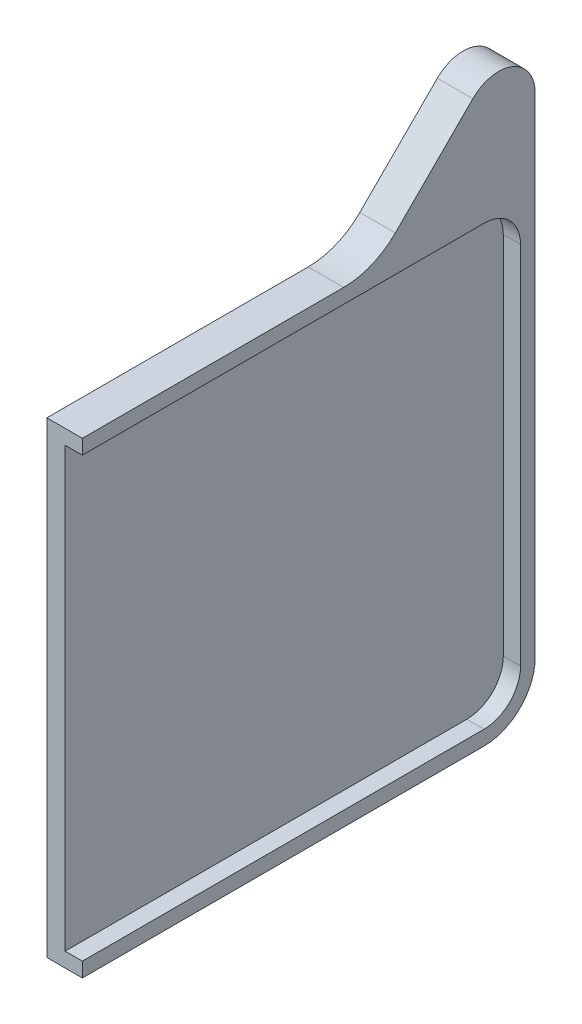
SolidWorks part; units mm, degrees
ref_plane "Front Plane" through (0, 0, 0) normal (0, 0, 1) x (1, 0, 0)
ref_plane "Top Plane" through (0, 0, 0) normal (0, 1, 0) x (1, 0, 0)
ref_plane "Right Plane" through (0, 0, 0) normal (1, 0, 0) x (0, 0, -1)
sketch "Sketch1" plane through (35.1028, 0, 0) normal (-1, 0, 0) x (0, 0, 1)
  line L0 (-114.3, 38.1) -> (-114.3, -38.1)
  line L1 (-114.3, 38.1) -> (-184.15, 38.1)
  line L2 (-190.5, 31.75) -> (-190.5, -31.75)
  line L3 (-184.15, -38.1) -> (-114.3, -38.1)
  line L4 (190.5, -31.75) -> (190.5, 31.75)
  line L5 (184.15, 38.1) -> (-184.15, 38.1)
  line L6 (-190.5, 31.75) -> (-190.5, -31.75)
  line L7 (-184.15, -38.1) -> (184.15, -38.1)
  line L8 (190.5, -31.75) -> (190.5, 31.75) construction
  line L9 (184.15, 38.1) -> (-184.15, 38.1) construction
  line L10 (-190.5, 31.75) -> (-190.5, -31.75) construction
  line L11 (-184.15, -38.1) -> (184.15, -38.1) construction
  arc A0 (-190.5, -31.75) -> (-184.15, -38.1) centre (-184.15, -31.75) ccw
  arc A1 (-190.5, 31.75) -> (-184.15, 38.1) centre (-184.15, 31.75) cw
  arc A4 (184.15, -38.1) -> (190.5, -31.75) centre (184.15, -31.75) ccw
  arc A5 (190.5, 31.75) -> (184.15, 38.1) centre (184.15, 31.75) ccw
  arc A6 (-184.15, 38.1) -> (-190.5, 31.75) centre (-184.15, 31.75) ccw
  arc A7 (-190.5, -31.75) -> (-184.15, -38.1) centre (-184.15, -31.75) ccw
  arc A8 (184.15, -38.1) -> (190.5, -31.75) centre (184.15, -31.75) ccw construction
  arc A9 (190.5, 31.75) -> (184.15, 38.1) centre (184.15, 31.75) ccw construction
  arc A10 (-184.15, 38.1) -> (-190.5, 31.75) centre (-184.15, 31.75) ccw construction
  arc A11 (-190.5, -31.75) -> (-184.15, -38.1) centre (-184.15, -31.75) ccw construction
  dimension "D2" = 76.2
  dimension "D1" = 0
extrude "Boss-Extrude1" add sketch "Sketch1" along normal blind 3.175 contours L0 L3 A0 L2 A1 L1
ref_plane "Plane1" through (35.1028, 38.1, -184.15) normal (0, 0, -1) x (-1, 0, 0)
sketch "Sketch4" plane through (31.9278, 0, 0) normal (-1, 0, 0) x (0, 0, 1)
  line L4 (-114.3, 38.1) -> (-184.15, 38.1)
  line L5 (-190.5, 31.75) -> (-190.5, -31.75)
  line L6 (-184.15, -38.1) -> (-114.3, -38.1)
  line L7 (-114.3, -38.1) -> (-114.3, 38.1)
  line L8 (-114.3, 38.1) -> (-184.15, 38.1)
  line L9 (-190.5, 31.75) -> (-190.5, -31.75)
  line L10 (-184.15, -38.1) -> (-114.3, -38.1)
  line L11 (-114.3, -38.1) -> (-114.3, 38.1) construction
  arc A2 (-184.15, 38.1) -> (-190.5, 31.75) centre (-184.15, 31.75) ccw
  arc A3 (-190.5, -31.75) -> (-184.15, -38.1) centre (-184.15, -31.75) ccw
  arc A4 (-184.15, 38.1) -> (-190.5, 31.75) centre (-184.15, 31.75) ccw
  arc A5 (-190.5, -31.75) -> (-184.15, -38.1) centre (-184.15, -31.75) ccw
  dimension "D1" = 0
extrude "Extrude-Thin1" add sketch "Sketch4" against normal up to surface (6.1722 mm away) thin
sketch "Sketch5" plane through (31.9278, 0, 0) normal (-1, 0, 0) x (0, 0, 1)
  line L0 (-177.8, 12.7) -> (-120.65, 12.7) construction
  line L1 (-177.8, 15.875) -> (-171.45, 15.875)
  line L2 (-177.8, 9.525) -> (-171.45, 9.525)
  line L3 (-171.45, 15.875) -> (-170.3501, 15.24)
  line L6 (-114.3, 0) -> (-193.04, 0) construction
  line L7 (-114.3, 40.64) -> (-114.3, -40.64) construction
  line L8 (-193.04, 31.75) -> (-193.04, -31.75) construction
  line L9 (-170.3501, 15.24) -> (-128.0999, 15.24)
  line L10 (-128.0999, 15.24) -> (-127, 15.875)
  line L11 (177.8, -15.875) -> (-177.8, -15.875)
  line L12 (-177.8, -22.225) -> (177.8, -22.225)
  line L13 (190.5, -31.75) -> (190.5, 31.75)
  line L14 (184.15, 38.1) -> (-184.15, 38.1)
  line L15 (-190.5, 31.75) -> (-190.5, -31.75)
  line L16 (-184.15, -38.1) -> (184.15, -38.1)
  line L17 (190.5, -31.75) -> (190.5, 31.75) construction
  line L18 (184.15, 38.1) -> (-184.15, 38.1) construction
  line L19 (-190.5, 31.75) -> (-190.5, -31.75) construction
  line L20 (-184.15, -38.1) -> (184.15, -38.1) construction
  line L22 (-177.8, -22.225) -> (177.8, -22.225) construction
  line L23 (177.8, 22.225) -> (-177.8, 22.225)
  line L24 (-177.8, 15.875) -> (177.8, 15.875)
  line L25 (177.8, 22.225) -> (-177.8, 22.225) construction
  line L26 (-177.8, 15.875) -> (177.8, 15.875) construction
  line L27 (-171.45, 9.525) -> (-170.3501, 10.16)
  line L28 (-170.3501, 10.16) -> (-128.0999, 10.16)
  line L29 (-128.0999, 10.16) -> (-127, 9.525)
  line L30 (-127, 15.875) -> (-120.65, 15.875)
  line L31 (-171.45, 15.875) -> (-127, 15.875) construction
  line L32 (-127, 9.525) -> (-120.65, 9.525)
  line L33 (-171.45, 9.525) -> (-127, 9.525) construction
  line L34 (-180.975, -12.7) -> (-180.975, 12.7) construction
  arc A0 (-177.8, 15.875) -> (-177.8, 9.525) centre (-177.8, 12.7) ccw
  arc A1 (-120.65, 9.525) -> (-120.65, 15.875) centre (-120.65, 12.7) ccw
  circle A5 centre (184.15, 31.75) radius 1.5875
  arc A6 (177.8, -22.225) -> (177.8, -15.875) centre (177.8, -19.05) ccw
  arc A7 (-177.8, -15.875) -> (-177.8, -22.225) centre (-177.8, -19.05) ccw
  arc A8 (184.15, -38.1) -> (190.5, -31.75) centre (184.15, -31.75) ccw
  arc A9 (190.5, 31.75) -> (184.15, 38.1) centre (184.15, 31.75) ccw
  arc A10 (-184.15, 38.1) -> (-190.5, 31.75) centre (-184.15, 31.75) ccw
  arc A11 (-190.5, -31.75) -> (-184.15, -38.1) centre (-184.15, -31.75) ccw
  arc A12 (184.15, -38.1) -> (190.5, -31.75) centre (184.15, -31.75) ccw construction
  arc A13 (190.5, 31.75) -> (184.15, 38.1) centre (184.15, 31.75) ccw construction
  arc A14 (-184.15, 38.1) -> (-190.5, 31.75) centre (-184.15, 31.75) ccw construction
  arc A15 (-190.5, -31.75) -> (-184.15, -38.1) centre (-184.15, -31.75) ccw construction
  arc A16 (177.8, -22.225) -> (177.8, -15.875) centre (177.8, -19.05) ccw construction
  arc A18 (177.8, 15.875) -> (177.8, 22.225) centre (177.8, 19.05) ccw
  arc A19 (-177.8, 22.225) -> (-177.8, 15.875) centre (-177.8, 19.05) ccw
  arc A20 (177.8, 15.875) -> (177.8, 22.225) centre (177.8, 19.05) ccw construction
  arc A21 (-177.8, 22.225) -> (-177.8, 15.875) centre (-177.8, 19.05) ccw construction
  circle A22 centre (184.15, 31.75) radius 1.5875 construction
  circle A23 centre (184.15, 0) radius 1.5875
  circle A24 centre (184.15, 0) radius 1.5875 construction
  circle A25 centre (184.15, -31.75) radius 1.5875
  circle A26 centre (184.15, -31.75) radius 1.5875 construction
  circle A27 centre (120.65, -31.75) radius 1.5875
  circle A28 centre (120.65, -31.75) radius 1.5875 construction
  circle A29 centre (120.65, 0) radius 1.5875
  circle A30 centre (120.65, 0) radius 1.5875 construction
  circle A31 centre (120.65, 31.75) radius 1.5875
  circle A32 centre (120.65, 31.75) radius 1.5875 construction
  circle A33 centre (-184.15, 31.75) radius 1.5875
  circle A34 centre (-184.15, 31.75) radius 1.5875 construction
  circle A35 centre (-174.625, 31.75) radius 1.5875
  circle A36 centre (-174.625, 31.75) radius 1.5875 construction
  circle A37 centre (-174.625, -31.75) radius 1.5875
  circle A38 centre (-174.625, -31.75) radius 1.5875 construction
  circle A39 centre (-184.15, -31.75) radius 1.5875
  circle A40 centre (-184.15, -31.75) radius 1.5875 construction
  point P2 (-149.225, 12.7)
  point P20 (-180.975, 12.7)
  point P21 (-117.475, 12.7)
  point P79 (0, 0)
  point P80 (-180.975, 0)
  point P81 (0, 0)
  point P82 (-180.975, 19.05)
  dimension "D3" = 6.35
  dimension "D1" = 63.5
  dimension "D16" = 6.35
  dimension "D17" = 30
  dimension "D18" = 30
  dimension "D19" = 25.4
  dimension "D20" = 0.635
  dimension "D2" = 0
  dimension "D4" = 0
  dimension "D5" = 0
  dimension "D6" = 0
  dimension "D7" = 0
  dimension "D8" = 0
  dimension "D9" = 0
  dimension "D10" = 0
  dimension "D11" = 0
  dimension "D12" = 0
  dimension "D13" = 0
  dimension "D14" = 0
  dimension "D15" = 0
extrude "Boss-Extrude2" add sketch "Sketch5" along normal blind 2.9972 contours A0 L2 L27 L28 L29 L32 A1 L30 L10 L9 L3 L1
fillet "Fillet1" radius 3.175 4 edges at (30.4292, 9.525, -171.45) (30.4292, 9.525, -127) (30.4292, 15.875, -127) (30.4292, 15.875, -171.45)
mirror "Mirror1" about plane through (0, 0, 0) normal (0, 1, 0) of "Fillet1", "Boss-Extrude2"
sketch "Sketch6" plane through (31.9278, 0, 0) normal (-1, 0, 0) x (0, 0, 1)
  line L0 (-193.04, 31.75) -> (-193.04, 53.34)
  line L1 (-182.1999, 57.8301) -> (-168.7295, 44.3597)
  line L2 (-114.3, 40.64) -> (-184.15, 40.64) construction
  line L7 (-114.3, -40.64) -> (-114.3, 40.64)
  line L8 (-114.3, 40.64) -> (-184.15, 40.64)
  line L9 (-193.04, 31.75) -> (-193.04, -31.75)
  line L10 (-184.15, -40.64) -> (-114.3, -40.64)
  line L11 (-114.3, -40.64) -> (-114.3, 40.64) construction
  line L12 (-114.3, 40.64) -> (-184.15, 40.64)
  line L13 (-193.04, 31.75) -> (-193.04, -31.75)
  line L14 (-184.15, -40.64) -> (-114.3, -40.64)
  arc A0 (-193.04, 53.34) -> (-182.1999, 57.8301) centre (-186.69, 53.34) cw
  arc A1 (-168.7295, 44.3597) -> (-159.7492, 40.64) centre (-159.7492, 53.34) ccw
  arc A4 (-184.15, 40.64) -> (-193.04, 31.75) centre (-184.15, 31.75) ccw
  arc A5 (-193.04, -31.75) -> (-184.15, -40.64) centre (-184.15, -31.75) ccw
  arc A6 (-184.15, 40.64) -> (-193.04, 31.75) centre (-184.15, 31.75) ccw
  arc A7 (-193.04, -31.75) -> (-184.15, -40.64) centre (-184.15, -31.75) ccw
  point P14 (-193.04, 31.278)
  arc M10 (-184.15, 40.64) -> (-193.04, 31.75) centre (-184.15, 31.75) ccw
  dimension "D1" = 6.35
  dimension "D2" = 12.7
  dimension "D3" = 45
  dimension "D5" = 12.7
  dimension "D4" = 0
extrude "Boss-Extrude3" add sketch "Sketch6" against normal up to surface (6.1722 mm away) contours A1 L1 A0 L0 L12 M10 up to face at (38.1, 0, -163.9327)
